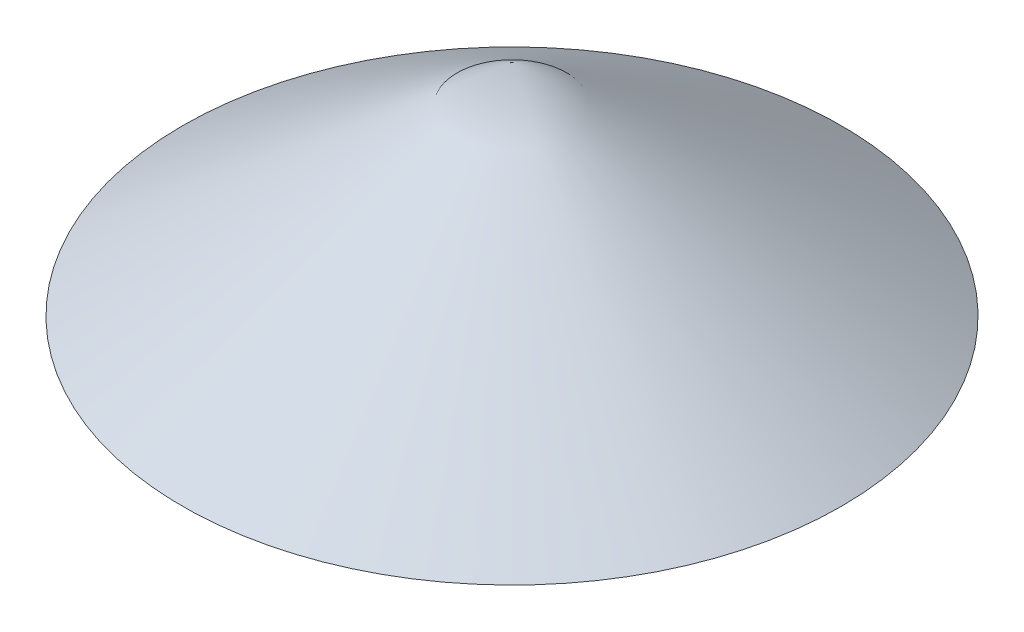
SolidWorks part; units mm, degrees
ref_plane "Front Plane" through (0, 0, 0) normal (0, 0, 1) x (1, 0, 0)
ref_plane "Top Plane" through (0, 0, 0) normal (0, 1, 0) x (1, 0, 0)
ref_plane "Right Plane" through (0, 0, 0) normal (1, 0, 0) x (0, 0, -1)
sketch "Sketch1" plane through (0, 0, 0) normal (0, 0, 1) x (1, 0, 0)
  line L0 (0, 0) -> (30, 0)
  line L1 (30, 0) -> (0, 20)
  line L2 (0, 20) -> (0, 0)
  dimension "D1" = 20
  dimension "D2" = 30
revolve "Revolve1" add sketch "Sketch1" angle 360 about L2
